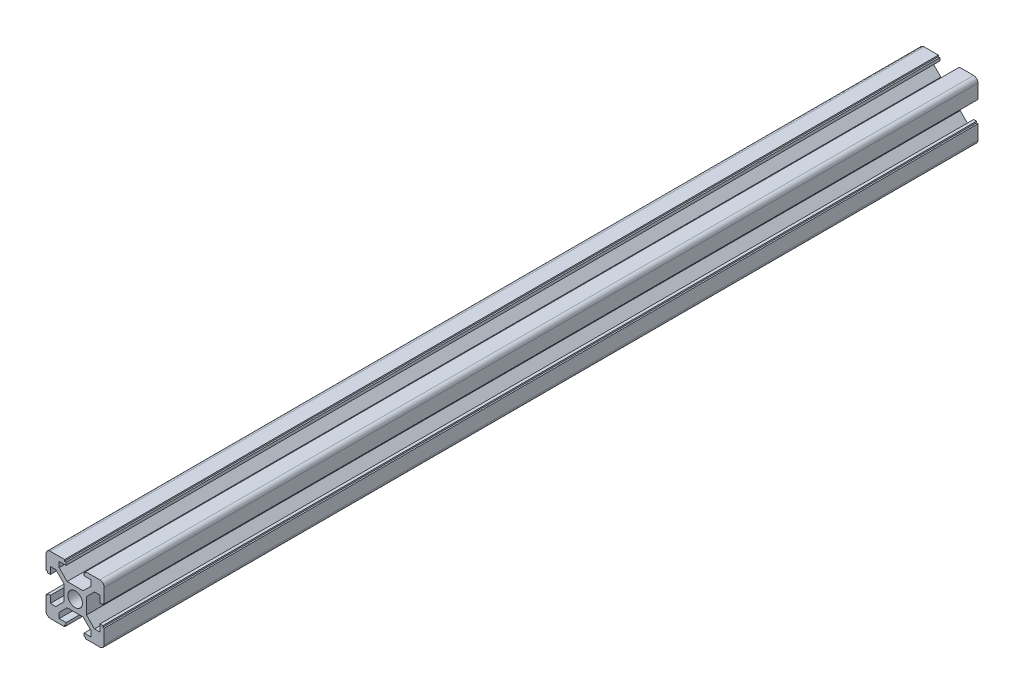
SolidWorks part; units mm, degrees
ref_plane "Plane1" through (0, 0, 0) normal (0, 0, 1) x (1, 0, 0)
ref_plane "Plane2" through (0, 0, 0) normal (0, 1, 0) x (1, 0, 0)
ref_plane "Plane3" through (0, 0, 0) normal (1, 0, 0) x (0, 0, -1)
sketch "Sketch1" plane through (0, 0, 0) normal (0, 0, 1) x (1, 0, 0)
  line L0 (-3.6, 10) -> (-3.6, 9.5)
  line L1 (-3.6, 9.5) -> (-3.1, 9.5)
  line L2 (-3.1, 9.5) -> (-3.1, 8.5)
  line L3 (-3.1, 8.5) -> (-5.5, 8.5)
  line L4 (-8.5, -10) -> (-3.6, -10)
  line L5 (-10, -8.5) -> (-10, -3.6)
  line L6 (8.5, 10) -> (3.6, 10)
  line L7 (10, 8.5) -> (10, 3.6)
  line L8 (0, 14.8756) -> (0, 0) construction
  line L9 (0, 0) -> (14.1675, 0) construction
  line L10 (-5.5, 8.5) -> (-5.5, 6.65)
  line L11 (-5.5, 6.65) -> (-2.75, 3.9)
  line L12 (-2.75, 3.9) -> (2.75, 3.9)
  line L13 (5.5, 6.65) -> (2.75, 3.9)
  line L14 (5.5, 8.5) -> (5.5, 6.65)
  line L15 (3.1, 8.5) -> (5.5, 8.5)
  line L16 (3.1, 9.5) -> (3.1, 8.5)
  line L17 (3.6, 9.5) -> (3.1, 9.5)
  line L18 (3.6, 10) -> (3.6, 9.5)
  line L19 (-3.6, 10) -> (-8.5, 10)
  line L20 (10, 3.6) -> (9.5, 3.6)
  line L21 (9.5, 3.6) -> (9.5, 3.1)
  line L22 (9.5, 3.1) -> (8.5, 3.1)
  line L23 (8.5, 3.1) -> (8.5, 5.5)
  line L24 (8.5, 5.5) -> (6.65, 5.5)
  line L25 (6.65, 5.5) -> (3.9, 2.75)
  line L26 (3.9, 2.75) -> (3.9, -2.75)
  line L27 (6.65, -5.5) -> (3.9, -2.75)
  line L28 (8.5, -5.5) -> (6.65, -5.5)
  line L29 (8.5, -3.1) -> (8.5, -5.5)
  line L30 (9.5, -3.1) -> (8.5, -3.1)
  line L31 (9.5, -3.6) -> (9.5, -3.1)
  line L32 (10, -3.6) -> (9.5, -3.6)
  line L33 (3.6, -10) -> (3.6, -9.5)
  line L34 (3.6, -9.5) -> (3.1, -9.5)
  line L35 (3.1, -9.5) -> (3.1, -8.5)
  line L36 (3.1, -8.5) -> (5.5, -8.5)
  line L37 (5.5, -8.5) -> (5.5, -6.65)
  line L38 (5.5, -6.65) -> (2.75, -3.9)
  line L39 (2.75, -3.9) -> (-2.75, -3.9)
  line L40 (-5.5, -6.65) -> (-2.75, -3.9)
  line L41 (-5.5, -8.5) -> (-5.5, -6.65)
  line L42 (-3.1, -8.5) -> (-5.5, -8.5)
  line L43 (-3.1, -9.5) -> (-3.1, -8.5)
  line L44 (-3.6, -9.5) -> (-3.1, -9.5)
  line L45 (-3.6, -10) -> (-3.6, -9.5)
  line L46 (-10, -3.6) -> (-9.5, -3.6)
  line L47 (-9.5, -3.6) -> (-9.5, -3.1)
  line L48 (-9.5, -3.1) -> (-8.5, -3.1)
  line L49 (-8.5, -3.1) -> (-8.5, -5.5)
  line L50 (-8.5, -5.5) -> (-6.65, -5.5)
  line L51 (-6.65, -5.5) -> (-3.9, -2.75)
  line L52 (-3.9, -2.75) -> (-3.9, 2.75)
  line L53 (-6.65, 5.5) -> (-3.9, 2.75)
  line L54 (-8.5, 5.5) -> (-6.65, 5.5)
  line L55 (-8.5, 3.1) -> (-8.5, 5.5)
  line L56 (-9.5, 3.1) -> (-8.5, 3.1)
  line L57 (-9.5, 3.6) -> (-9.5, 3.1)
  line L58 (-10, 3.6) -> (-9.5, 3.6)
  line L59 (3.6, -10) -> (8.5, -10)
  line L60 (-10, 3.6) -> (-10, 8.5)
  line L61 (10, -3.6) -> (10, -8.5)
  circle A0 centre (0, 0) radius 2.5
  arc A1 (-10, 8.5) -> (-8.5, 10) centre (-8.5, 8.5) cw
  arc A2 (10, 8.5) -> (8.5, 10) centre (8.5, 8.5) ccw
  arc A3 (-8.5, -10) -> (-10, -8.5) centre (-8.5, -8.5) cw
  arc A4 (8.5, -10) -> (10, -8.5) centre (8.5, -8.5) ccw
  point P0 (-10, 0)
  point P1 (10, 0)
  point P2 (0, 10)
  point P3 (0, -10)
  point P4 (0, 0)
  point P5 (-10, -10)
  point P6 (10, -10)
  point P7 (10, 10)
  point P8 (-10, 10)
  point P36 (-10, 10)
  point P39 (10, 10)
extrude "凸台-拉伸1" add sketch "Sketch1" along normal blind 300
